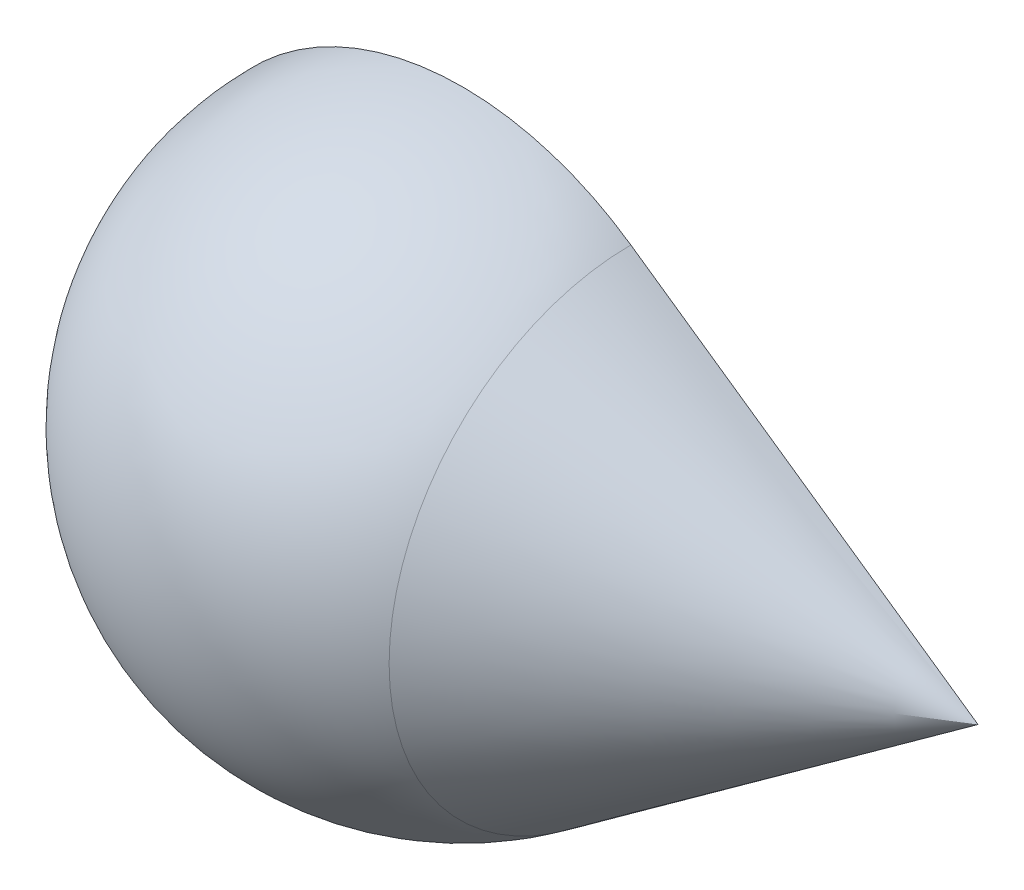
SolidWorks part; units mm, degrees
material "1060 合金"
ref_plane "前视基准面" through (0, 0, 0) normal (0, 0, 1) x (1, 0, 0)
ref_plane "上视基准面" through (0, 0, 0) normal (0, 1, 0) x (1, 0, 0)
ref_plane "右视基准面" through (0, 0, 0) normal (1, 0, 0) x (0, 0, -1)
sketch "草图1" plane through (0, 0, 0) normal (0, 0, 1) x (1, 0, 0)
  line L0 (0, 0) -> (70, 0) construction
  line L1 (70, 0) -> (22.8571, 32.8261)
  line L2 (70, 0) -> (22.8571, -32.8261)
  line L3 (70, 0) -> (-40, 0)
  arc A0 (22.8571, 32.8261) -> (22.8571, -32.8261) centre (0, 0) ccw
  point P1 (0, -40)
  point P3 (0, 40)
  dimension "D1" = 80
  dimension "D2" = 70
revolve "旋转6" add sketch "草图1" angle 180 about L0
